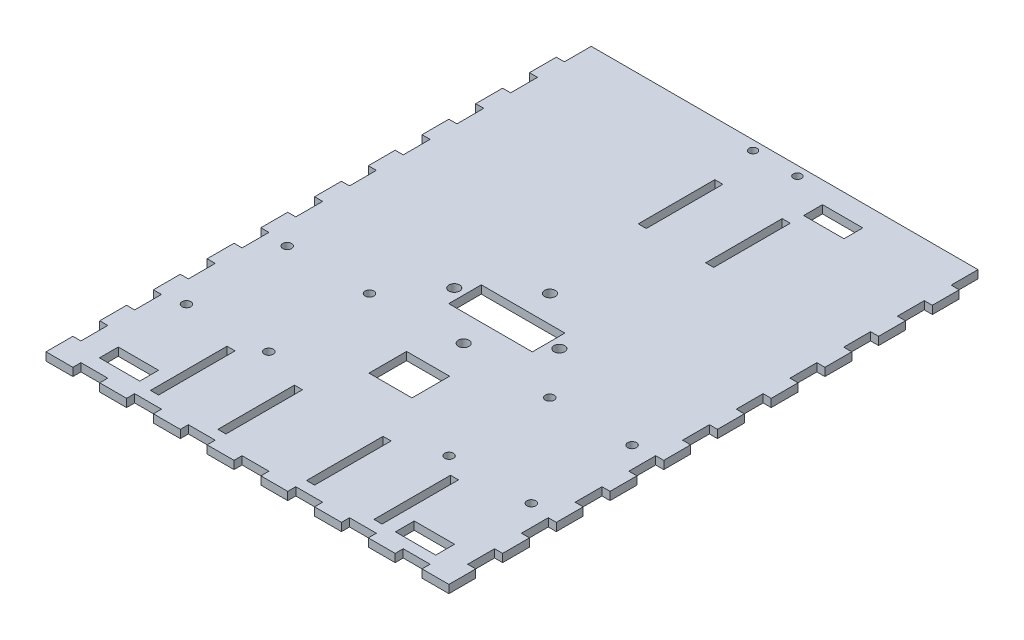
SolidWorks part; units mm, degrees
ref_plane "Plano frontal" through (0, 0, 0) normal (0, 0, 1) x (1, 0, 0)
ref_plane "Plano superior" through (0, 0, 0) normal (0, 1, 0) x (1, 0, 0)
ref_plane "Plano direito" through (0, 0, 0) normal (1, 0, 0) x (0, 0, -1)
sketch "mdfEsb" plane through (0, 0, 0) normal (0, 1, 0) x (1, 0, 0)
  line L1 (0, 0) -> (150, 0)
  line L2 (0, 0) -> (0, 200)
  line L3 (0, 200) -> (150, 200)
  line L4 (150, 0) -> (150, 200)
  dimension "D1" = 200
  dimension "D2" = 150
extrude "mdf" add sketch "mdfEsb" along normal blind 3
sketch "ldrEsb" plane through (0, 3, 0) normal (0, 1, 0) x (1, 0, 0)
  line L0 (75, 200) -> (75, 0) construction
  line L1 (31.9, 35.5) -> (34.9, 35.5)
  line L2 (31.9, 35.5) -> (31.9, 7)
  line L3 (31.9, 7) -> (34.9, 7)
  line L4 (34.9, 35.5) -> (34.9, 7)
  line L5 (57, 35.5) -> (60, 35.5)
  line L6 (57, 35.5) -> (57, 7)
  line L7 (57, 7) -> (60, 7)
  line L8 (60, 35.5) -> (60, 7)
  line L9 (0, 0) -> (150, 0) construction
  line L10 (150, 200) -> (0, 200) construction
  line L11 (90, 35.5) -> (90, 7)
  line L12 (93, 7) -> (90, 7)
  line L13 (93, 35.5) -> (93, 7)
  line L14 (93, 35.5) -> (90, 35.5)
  line L15 (115.1, 35.5) -> (115.1, 7)
  line L16 (118.1, 7) -> (115.1, 7)
  line L17 (118.1, 35.5) -> (118.1, 7)
  line L18 (118.1, 35.5) -> (115.1, 35.5)
  line L19 (72, 151.5) -> (69, 151.5)
  line L24 (94.1, 180) -> (97.1, 180)
  line L25 (94.1, 180) -> (94.1, 151.5)
  line L26 (94.1, 151.5) -> (97.1, 151.5)
  line L27 (97.1, 180) -> (97.1, 151.5)
  line L28 (69, 180) -> (69, 151.5)
  line L29 (72, 180) -> (69, 180)
  line L30 (72, 180) -> (72, 151.5)
  line L31 (123.1, 14) -> (138.1, 14)
  line L36 (26.9, 8) -> (11.9, 8)
  line L37 (26.9, 8) -> (26.9, 15)
  line L38 (26.9, 15) -> (11.9, 15)
  line L39 (11.9, 8) -> (11.9, 15)
  line L40 (97.1, 192) -> (112.1, 192)
  line L41 (97.1, 192) -> (97.1, 185)
  line L42 (97.1, 185) -> (112.1, 185)
  line L43 (112.1, 192) -> (112.1, 185)
  line L44 (138.1, 7) -> (138.1, 14)
  line L45 (123.1, 7) -> (138.1, 7)
  line L46 (123.1, 7) -> (123.1, 14)
  dimension "D1" = 28.5
  dimension "D2" = 22.1
  dimension "D3" = 3
  dimension "D4" = 3
  dimension "D5" = 15
  dimension "D6" = 7
  dimension "D7" = 28.5
  dimension "D8" = 3
  dimension "D9" = 22.1
  dimension "D10" = 20
  dimension "D11" = 15
  dimension "D12" = 7
  dimension "D13" = 5
  dimension "D14" = 3
  dimension "D15" = 7
  dimension "D16" = 7
  dimension "D17" = 28.5
  dimension "D18" = 22.1
  dimension "D19" = 15
  dimension "D20" = 3
  dimension "D21" = 3
  dimension "D22" = 5
  dimension "D23" = 7
  dimension "D24" = 15
  dimension "D26" = 3
  dimension "D27" = 15
  dimension "D28" = 8
  dimension "D29" = 5
extrude "ldrBuracos" cut sketch "ldrEsb" against normal blind 3
sketch "corEsb" plane through (0, 3, 0) normal (0, 1, 0) x (1, 0, 0)
  line L0 (75, 0) -> (75, 200) construction
  line L1 (59.44, 102.63) -> (90.56, 102.63)
  line L2 (59.44, 102.63) -> (59.44, 90.5)
  line L3 (59.44, 90.5) -> (90.56, 90.5)
  line L4 (90.56, 102.63) -> (90.56, 90.5)
  line L5 (0, 0) -> (150, 0) construction
  line L6 (150, 200) -> (0, 200) construction
  circle A0 centre (75, 112.63) radius 2
  circle A1 centre (75, 80.5) radius 2
  circle A2 centre (94.56, 96.565) radius 2
  circle A3 centre (55.44, 96.565) radius 2
  point P10 (75, 102.63)
  point P20 (59.44, 96.565)
  point P22 (90.56, 96.565)
  dimension "D3" = 4
  dimension "D4" = 4
  dimension "D5" = 4
  dimension "D6" = 4
  dimension "D1" = 31.12
  dimension "D2" = 12.13
  dimension "D7" = 4
  dimension "D8" = 4
  dimension "D9" = 10
  dimension "D10" = 10
  dimension "D11" = 45
extrude "corBuracos" cut sketch "corEsb" against normal blind 3
sketch "EncaixesEsb" plane through (0, 3, 0) normal (0, 1, 0) x (1, 0, 0)
  line L0 (0, 0) -> (150, 0) construction
  line L1 (10, 0) -> (20, 0)
  line L2 (10, 0) -> (10, 3)
  line L3 (10, 3) -> (20, 3)
  line L4 (20, 0) -> (20, 3)
  line L5 (0, 30) -> (0, 40)
  line L22 (0, 30) -> (3, 30)
  line L31 (0, 200) -> (0, 0) construction
  line L32 (0, 10) -> (3, 10)
  line L33 (0, 10) -> (0, 20)
  line L34 (0, 20) -> (3, 20)
  line L35 (3, 10) -> (3, 20)
  line L36 (3, 30) -> (3, 40)
  line L37 (0, 40) -> (3, 40)
  line L38 (0, 50) -> (0, 60)
  line L39 (0, 50) -> (3, 50)
  line L40 (3, 50) -> (3, 60)
  line L41 (0, 60) -> (3, 60)
  line L42 (0, 70) -> (0, 80)
  line L43 (0, 70) -> (3, 70)
  line L44 (3, 70) -> (3, 80)
  line L45 (0, 80) -> (3, 80)
  line L46 (0, 90) -> (0, 100)
  line L47 (0, 90) -> (3, 90)
  line L48 (3, 90) -> (3, 100)
  line L49 (0, 100) -> (3, 100)
  line L50 (0, 110) -> (0, 120)
  line L51 (0, 110) -> (3, 110)
  line L52 (3, 110) -> (3, 120)
  line L53 (0, 120) -> (3, 120)
  line L54 (0, 130) -> (0, 140)
  line L55 (0, 130) -> (3, 130)
  line L56 (3, 130) -> (3, 140)
  line L57 (0, 140) -> (3, 140)
  line L58 (0, 150) -> (0, 160)
  line L59 (0, 150) -> (3, 150)
  line L60 (3, 150) -> (3, 160)
  line L61 (0, 160) -> (3, 160)
  line L62 (0, 170) -> (0, 180)
  line L63 (0, 170) -> (3, 170)
  line L64 (3, 170) -> (3, 180)
  line L65 (0, 180) -> (3, 180)
  line L66 (0, 190) -> (0, 200)
  line L67 (0, 190) -> (3, 190)
  line L68 (3, 190) -> (3, 200)
  line L69 (0, 200) -> (3, 200)
  line L70 (30, 0) -> (30, 3)
  line L71 (30, 0) -> (40, 0)
  line L72 (40, 0) -> (40, 3)
  line L73 (30, 3) -> (40, 3)
  line L74 (50, 0) -> (50, 3)
  line L75 (50, 0) -> (60, 0)
  line L76 (60, 0) -> (60, 3)
  line L77 (50, 3) -> (60, 3)
  line L78 (70, 0) -> (70, 3)
  line L79 (70, 0) -> (80, 0)
  line L80 (80, 0) -> (80, 3)
  line L81 (70, 3) -> (80, 3)
  line L82 (90, 0) -> (90, 3)
  line L83 (90, 0) -> (100, 0)
  line L84 (100, 0) -> (100, 3)
  line L85 (90, 3) -> (100, 3)
  line L86 (110, 0) -> (110, 3)
  line L87 (110, 0) -> (120, 0)
  line L88 (120, 0) -> (120, 3)
  line L89 (110, 3) -> (120, 3)
  line L90 (130, 0) -> (130, 3)
  line L91 (130, 0) -> (140, 0)
  line L92 (140, 0) -> (140, 3)
  line L93 (130, 3) -> (140, 3)
  line L94 (10, 0) -> (30, 0) construction
  line L125 (147, 30) -> (147, 40)
  line L126 (147, 30) -> (150, 30)
  line L127 (147, 10) -> (150, 10)
  line L128 (147, 10) -> (147, 20)
  line L129 (147, 20) -> (150, 20)
  line L130 (150, 10) -> (150, 20)
  line L131 (150, 30) -> (150, 40)
  line L132 (147, 40) -> (150, 40)
  line L133 (147, 50) -> (147, 60)
  line L134 (147, 50) -> (150, 50)
  line L135 (150, 50) -> (150, 60)
  line L136 (147, 60) -> (150, 60)
  line L137 (147, 70) -> (147, 80)
  line L138 (147, 70) -> (150, 70)
  line L139 (150, 70) -> (150, 80)
  line L140 (147, 80) -> (150, 80)
  line L141 (147, 90) -> (147, 100)
  line L142 (147, 90) -> (150, 90)
  line L143 (150, 90) -> (150, 100)
  line L144 (147, 100) -> (150, 100)
  line L145 (147, 110) -> (147, 120)
  line L146 (147, 110) -> (150, 110)
  line L147 (150, 110) -> (150, 120)
  line L148 (147, 120) -> (150, 120)
  line L149 (147, 130) -> (147, 140)
  line L150 (147, 130) -> (150, 130)
  line L151 (150, 130) -> (150, 140)
  line L152 (147, 140) -> (150, 140)
  line L153 (147, 150) -> (147, 160)
  line L154 (147, 150) -> (150, 150)
  line L155 (150, 150) -> (150, 160)
  line L156 (147, 160) -> (150, 160)
  line L157 (147, 170) -> (147, 180)
  line L158 (147, 170) -> (150, 170)
  line L159 (150, 170) -> (150, 180)
  line L160 (147, 180) -> (150, 180)
  line L161 (147, 190) -> (147, 200)
  line L162 (147, 190) -> (150, 190)
  line L163 (150, 190) -> (150, 200)
  line L164 (147, 200) -> (150, 200)
  line L165 (150, 0) -> (150, 200) construction
  dimension "D1" = 10
  dimension "D2" = 3
  dimension "D3" = 10
  dimension "D4" = 7
  dimension "D5" = 20
  dimension "D7" = 2
  dimension "D16" = 3
  dimension "D17" = 10
  dimension "D18" = 10
  dimension "D20" = 10
  dimension "D19" = 10
extrude "Encaixe" cut sketch "EncaixesEsb" against normal blind 3
sketch "AcoplMotorEsb" plane through (0, 3, 0) normal (0, 1, 0) x (1, 0, 0)
  line L0 (75, 3) -> (75, 200) construction
  line L1 (80, 3) -> (70, 3) construction
  line L3 (118.1, 35.5) -> (115.1, 35.5) construction
  line L4 (147, 40) -> (147, 30) construction
  line L5 (147, 200) -> (3, 200) construction
  line L6 (10.8, 41.5) -> (10.8, 79) construction
  line L7 (10.8, 79) -> (10.8, 60.25) construction
  line L8 (10.8, 60.25) -> (161.2843, 60.25) construction
  line L10 (67, 53.25) -> (83, 53.25)
  line L11 (67, 53.25) -> (67, 67.25)
  line L12 (67, 67.25) -> (83, 67.25)
  line L13 (83, 53.25) -> (83, 67.25)
  line L14 (67, 53.25) -> (83, 67.25) construction
  line L15 (67, 67.25) -> (83, 53.25) construction
  circle A0 centre (108.56, 41.5) radius 1.65
  circle A1 centre (108.56, 79) radius 1.65
  circle A2 centre (139.2, 41.5) radius 1.65
  circle A3 centre (139.2, 79) radius 1.65
  circle A4 centre (10.8, 79) radius 1.65
  circle A5 centre (10.8, 41.5) radius 1.65
  circle A6 centre (41.44, 79) radius 1.65
  circle A7 centre (41.44, 41.5) radius 1.65
  circle A8 centre (94.56, 96.565) radius 2 construction
  point P14 (75, 60.25)
  dimension "D1" = 3.3
  dimension "D3" = 37.5
  dimension "D4" = 7.8
  dimension "D5" = 14
  dimension "D2" = 6
  dimension "D6" = 14
  dimension "D7" = 16
extrude "AcoplMotor" cut sketch "AcoplMotorEsb" against normal blind 3
sketch "CasterFurosEsb" plane through (0, 3, 0) normal (0, 1, 0) x (1, 0, 0)
  line L0 (75, 200) -> (75, 3) construction
  line L1 (147, 200) -> (3, 200) construction
  line L2 (80, 3) -> (70, 3) construction
  circle A0 centre (66.75, 196.5) radius 1.5
  circle A1 centre (83.25, 196.5) radius 1.5
  dimension "D1" = 3
  dimension "D2" = 3.5
  dimension "D3" = 8.25
extrude "CasterFuros" cut sketch "CasterFurosEsb" against normal blind 3
